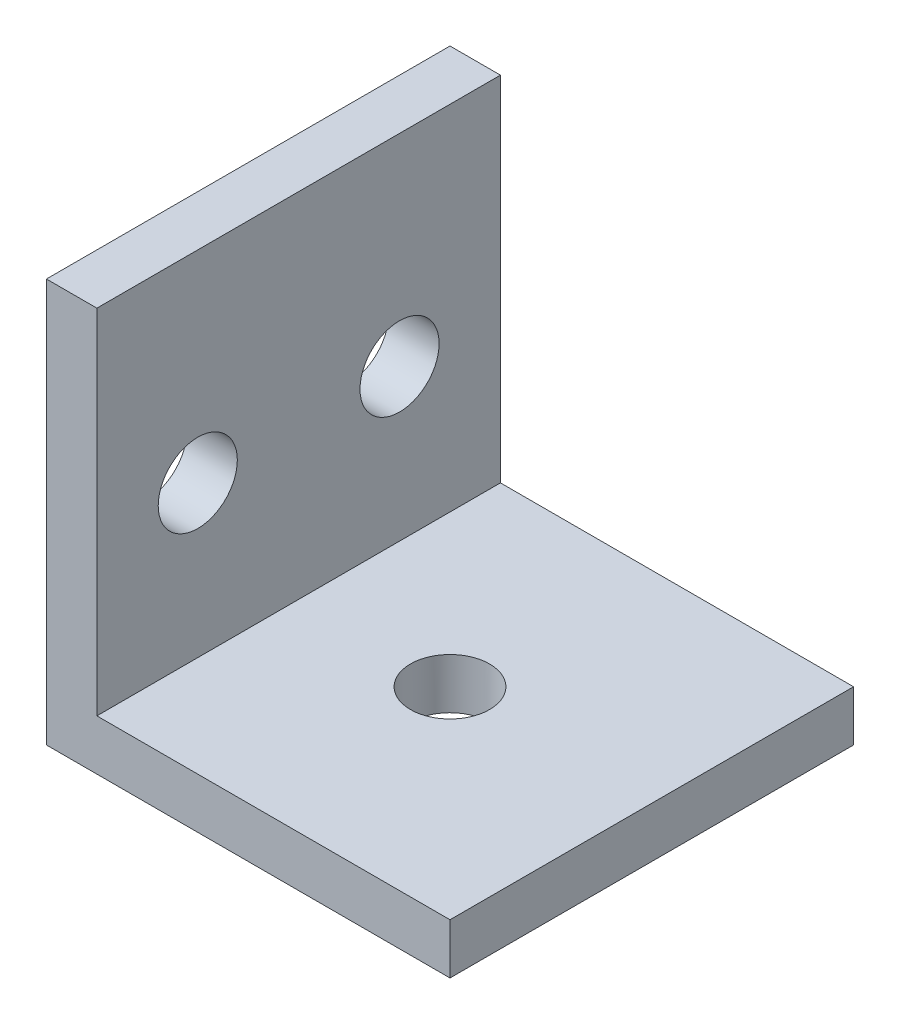
SolidWorks part; units mm, degrees
ref_plane "Front Plane" through (0, 0, 0) normal (0, 0, 1) x (1, 0, 0)
ref_plane "Top Plane" through (0, 0, 0) normal (0, 1, 0) x (1, 0, 0)
ref_plane "Right Plane" through (0, 0, 0) normal (1, 0, 0) x (0, 0, -1)
sketch "Sketch1" plane through (0, 0, 0) normal (0, 0, 1) x (1, 0, 0)
  line L0 (0, 0) -> (0, 25.4)
  line L1 (0, 25.4) -> (3.175, 25.4)
  line L2 (3.175, 25.4) -> (3.175, 3.175)
  line L3 (3.175, 3.175) -> (25.4, 3.175)
  line L4 (25.4, 3.175) -> (25.4, 0)
  line L5 (25.4, 0) -> (0, 0)
  dimension "D1" = 3.175
  dimension "D2" = 25.4
extrude "Boss-Extrude1" add sketch "Sketch1" along normal mid plane 25.4
sketch "Sketch3" plane through (0, 3.175, 0) normal (0, 1, 0) x (1, 0, 0)
  line L0 (0, -12.7) -> (25.4, -12.7) construction
  line L1 (25.4, -12.7) -> (25.4, 12.7) construction
  circle A0 centre (12.7, 0) radius 2.4892
  point P4 (12.7, -12.7)
  point P7 (25.4, 0)
  dimension "D1" = 4.9784
extrude "Cut-Extrude1" cut sketch "Sketch3" against normal through all both and the other way through all
sketch "Sketch4" plane through (3.175, 0, 0) normal (1, 0, 0) x (0, 0, -1)
  line L0 (12.7, 3.175) -> (12.7, 25.4) construction
  line L1 (12.7, 25.4) -> (12.7, 0) construction
  circle A0 centre (-6.35, 12.7) radius 2.4892
  circle A1 centre (6.35, 12.7) radius 2.4892
  point P8 (12.7, 12.7)
  dimension "D1" = 4.9784
  dimension "D2" = 6.35
  dimension "D3" = 12.7
extrude "Cut-Extrude2" cut sketch "Sketch4" against normal through all both and the other way through all
